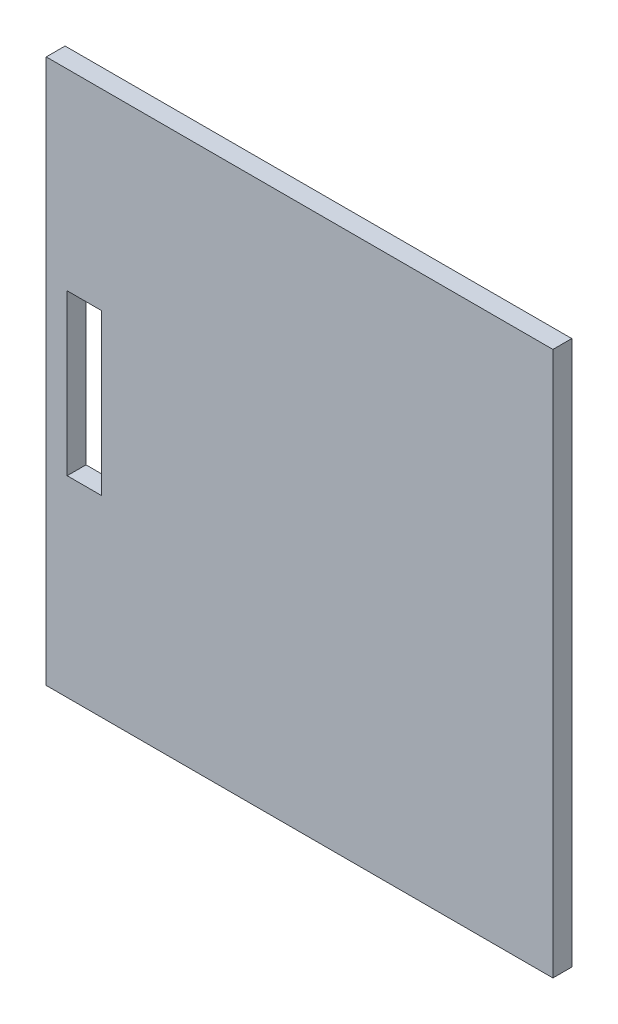
SolidWorks part; units mm, degrees
ref_plane "Front Plane" through (0, 0, 0) normal (0, 0, 1) x (1, 0, 0)
ref_plane "Top Plane" through (0, 0, 0) normal (0, 1, 0) x (1, 0, 0)
ref_plane "Right Plane" through (0, 0, 0) normal (1, 0, 0) x (0, 0, -1)
sketch "Sketch1" plane through (0, 0, 0) normal (0, 0, 1) x (1, 0, 0)
  line L0 (-60.5, 0) -> (-51.4, 0) construction
  line L1 (-60.5, -65) -> (60.5, -65)
  line L2 (-60.5, -65) -> (-60.5, 65)
  line L3 (-60.5, 65) -> (60.5, 65)
  line L4 (60.5, -65) -> (60.5, 65)
  line L5 (-60.5, -65) -> (60.5, 65) construction
  line L6 (-60.5, 65) -> (60.5, -65) construction
  line L7 (-47.3, -19.125) -> (-47.3, 19.125)
  line L8 (-47.3, -19.125) -> (-55.5, -19.125)
  line L9 (-47.3, 19.125) -> (-55.5, 19.125)
  line L10 (-55.5, -19.125) -> (-55.5, 19.125)
  line L11 (-47.3, -19.125) -> (-55.5, 19.125) construction
  line L12 (-47.3, 19.125) -> (-55.5, -19.125) construction
  point P0 (0, 0)
  dimension "D1" = 121
  dimension "D2" = 130
  dimension "D3" = 9.1
  dimension "D4" = 38.25
  dimension "D5" = 8.2
extrude "Boss-Extrude1" add sketch "Sketch1" along normal blind 4.5
